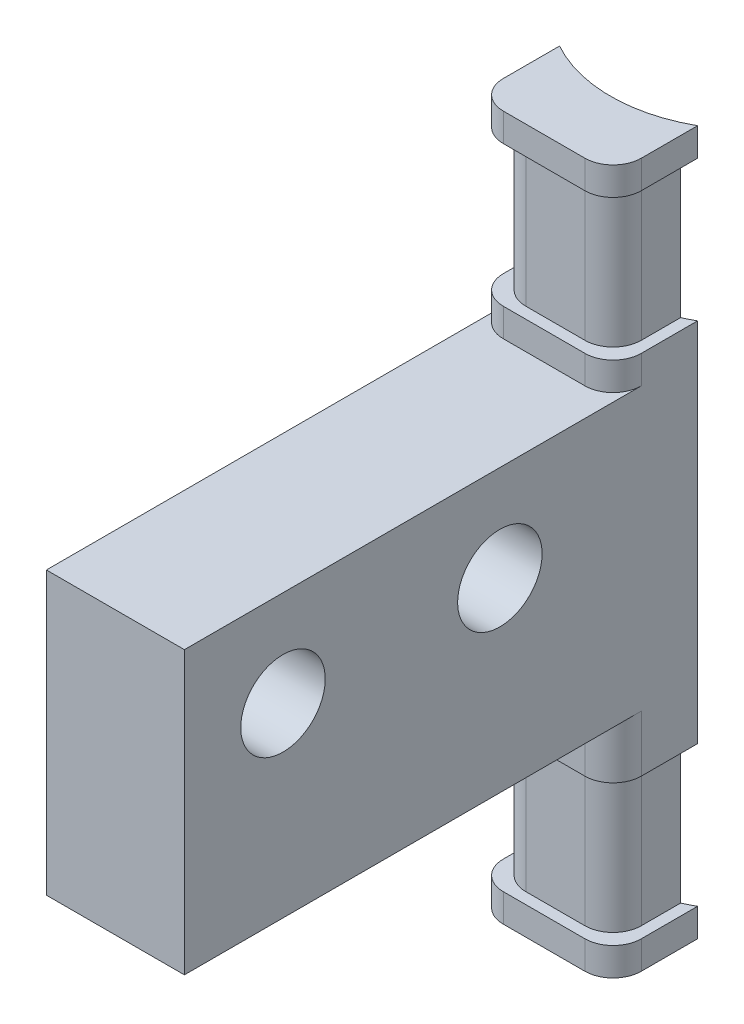
SolidWorks part; units mm, degrees
ref_plane "Front Plane" through (0, 0, 0) normal (0, 0, 1) x (1, 0, 0)
ref_plane "Top Plane" through (0, 0, 0) normal (0, 1, 0) x (1, 0, 0)
ref_plane "Right Plane" through (0, 0, 0) normal (1, 0, 0) x (0, 0, -1)
sketch "Sketch2" plane through (0, 0, 0) normal (0, 0, 1) x (1, 0, 0)
  line L1 (0, 0) -> (6.223, 0)
  line L2 (0, 0) -> (0, 12.7)
  line L3 (0, 12.7) -> (6.223, 12.7)
  line L4 (6.223, 0) -> (6.223, 12.7)
  line L5 (0, 0) -> (6.223, 12.7) construction
  line L6 (0, 12.7) -> (6.223, 0) construction
  point P4 (3.1115, 6.35)
  dimension "D1" = 6.223
  dimension "D2" = 12.7
extrude "Boss-Extrude1" add sketch "Sketch2" along normal blind 19.3294
sketch "Sketch3" plane through (6.223, 0, 0) normal (1, 0, 0) x (0, 0, -1)
  line L0 (-19.3294, 0) -> (0, 0) construction
  line L1 (-19.3294, 0) -> (-19.3294, 12.7) construction
  circle A0 centre (-14.8844, 8.382) radius 1.905
  circle A1 centre (-5.1054, 8.382) radius 1.905
  dimension "D2" = 8.382
  dimension "D3" = 3.81
  dimension "D4" = 3.81
  dimension "D6" = 9.779
  dimension "D1" = 8.382
  dimension "D5" = 4.445
extrude "Cut-Extrude1" cut sketch "Sketch3" against normal blind 19.3294
sketch "Sketch4" plane through (0, 12.7, 0) normal (0, 1, 0) x (1, 0, 0)
  line L0 (6.223, 3.81) -> (6.223, 0)
  line L1 (6.223, 0) -> (0, 0)
  line L2 (0, 0) -> (0, 3.81)
  arc A0 (6.223, 3.81) -> (0, 3.81) centre (3.1115, 9.3454) cw
  dimension "D1" = 6.35
  dimension "D2" = 3.81
  dimension "D3" = 3.81
extrude "Boss-Extrude2" add sketch "Sketch4" along normal blind 8.89 and the other way blind 22.86
sketch "Sketch5" plane through (0, 21.59, 0) normal (0, 1, 0) x (1, 0, 0)
  line L0 (5.715, 0.508) -> (5.715, 3.0008)
  line L1 (0.508, 3.0008) -> (0.508, 0.508)
  line L2 (0.508, 0.508) -> (5.715, 0.508)
  line L3 (0, 3.81) -> (0, 0)
  line L4 (0, 0) -> (6.223, 0)
  line L5 (6.223, 0) -> (6.223, 3.81)
  line L6 (0, 3.81) -> (0, 0)
  line L7 (0, 0) -> (6.223, 0)
  line L8 (6.223, 0) -> (6.223, 3.81)
  line L9 (5.715, 3.0008) -> (5.715, 3.5537)
  line L10 (0.508, 3.0008) -> (0.508, 3.5537)
  arc A1 (0, 3.81) -> (6.223, 3.81) centre (3.1115, 9.3454) ccw
  arc A2 (0, 3.81) -> (0.508, 3.5537) centre (3.1115, 9.3454) ccw
  arc A3 (0.508, 3.0008) -> (5.715, 3.0008) centre (3.1115, 9.3454) ccw construction
  arc A4 (5.715, 3.5537) -> (6.223, 3.81) centre (3.1115, 9.3454) ccw
  arc A5 (0, 3.81) -> (6.223, 3.81) centre (3.1115, 9.3454) ccw construction
  dimension "D1" = 0
  dimension "D2" = 0.508
extrude "Cut-Extrude2" cut sketch "Sketch5" against normal blind 6.35 from offset 1.27 offset against normal yes
ref_plane "Plane1" through (0, 5.715, 0) normal (0, 1, 0) x (1, 0, 0)
mirror "Mirror1" about plane through (0, 5.715, 0) normal (0, 1, 0) of "Cut-Extrude2"
fillet "Fillet1" radius 1.27 12 edges at (6.223, -9.525, 0) (5.715, -5.715, -0.508) (6.223, -1.27, 0) (0, -9.525, 0) (0.508, -5.715, -0.508) (0, -1.27, 0) (6.223, 13.335, 0) (5.715, 17.145, -0.508) (6.223, 20.955, 0) (0, 13.335, 0) (0.508, 17.145, -0.508) (0, 20.955, 0)
